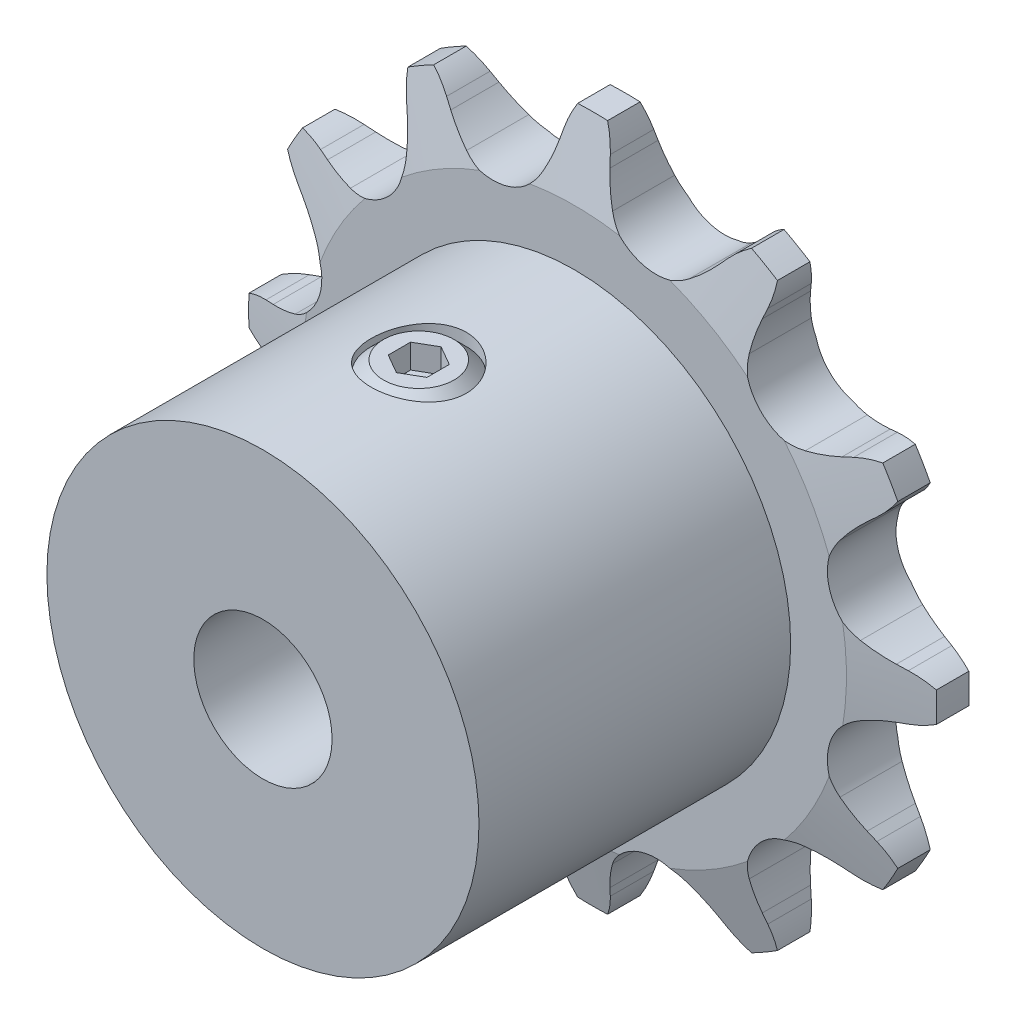
SolidWorks part; units mm, degrees
ref_plane "Front Plane" through (0, 0, 0) normal (0, 0, 1) x (1, 0, 0)
ref_plane "Top Plane" through (0, 0, 0) normal (0, 1, 0) x (1, 0, 0)
ref_plane "Right Plane" through (0, 0, 0) normal (1, 0, 0) x (0, 0, -1)
sketch "Sketch0" plane through (0, 0, 0) normal (0, 0, 1) x (1, 0, 0)
  line L0 (1.8732, -6.9911) -> (0, 0) construction
  line L1 (0, 0) -> (5.1178, -5.1178) construction
  line L2 (0, 0) -> (-1.8732, -6.9911) construction
  line L3 (1.8732, -6.9911) -> (5.1178, -5.1178) construction
  line L4 (1.8732, -6.9911) -> (-1.8732, -6.9911) construction
  line L5 (3.2269, -6.6528) -> (3.077, -6.4844)
  line L6 (1.8732, -6.9911) -> (0, -7.493) construction
  line L7 (0.5318, -7.3749) -> (0.5774, -7.1541)
  line L8 (0, -6.9911) -> (0, -8.115) construction
  line L9 (2.554, -6.0189) -> (0.8243, -8.4891) construction
  line L10 (0, 0) -> (0, -6.9911) construction
  line L11 (3.077, -6.4844) -> (0.8243, -8.4891) construction
  line L12 (0, -8.115) -> (0, -8.3482) construction
  line L13 (4.6449, -5.3909) -> (3.2269, -6.6528) construction
  circle A0 centre (0, 0) radius 8.115 construction
  circle A1 centre (0, 0) radius 7.2377 construction
  arc A2 (-1.6812, -8.8559) -> (5.8839, -6.8289) centre (0, 0) ccw
  circle A3 centre (0, 0) radius 8.3482 construction
  circle A4 centre (1.8732, -6.9911) radius 1.143 construction
  arc A7 (2.554, -6.0189) -> (0.7976, -6.4895) centre (1.8732, -6.9911) ccw
  circle A8 centre (1.8732, -6.9911) radius 1.1868 construction
  arc A9 (3.2269, -6.6528) -> (5.8839, -6.8289) centre (4.6449, -5.3909) ccw
  arc A10 (3.077, -6.4844) -> (2.554, -6.0189) centre (0.8243, -8.4891) ccw
  arc A11 (0.5318, -7.3749) -> (-1.6812, -8.8559) centre (-1.3271, -6.9911) cw
  arc A12 (0.5774, -7.1541) -> (0.7976, -6.4895) centre (3.5307, -7.7639) cw
  dimension "D1" = 1.1868
  dimension "Dr" = 2.286
  dimension "Ds" = 2.3736
  dimension "R" = 1.1868
  dimension "Pitch" = 3.7465
  dimension "A" = 40
  dimension "360/N" = 30
  dimension "B" = 13.333
  dimension "ab" = 3.2004
  dimension "J" = 1.1239
  dimension "ac" = 1.8288
sketch "Sketch1" plane through (0, 0, 0) normal (1, 0, 0) x (0, 0, -1)
  line L0 (0.7874, 0) -> (-0.7874, 0)
  line L1 (-0.7874, 0) -> (-0.7874, 6.2418)
  line L2 (-0.7874, 6.2418) -> (-0.3191, 8.115)
  line L3 (-0.3191, 8.115) -> (0.3191, 8.115)
  line L4 (0.3191, 8.115) -> (0.7874, 6.2418)
  line L5 (0.7874, 6.2418) -> (0.7874, 0)
  line L7 (0, 8.115) -> (0, 0) construction
  line L8 (-0.7874, 6.2418) -> (0.7874, 6.2418) construction
  line L9 (0, 8.115) -> (0, -8.115) construction
  line L10 (-0.7874, 6.2418) -> (-0.7874, 8.115) construction
  line L11 (-0.7874, 8.115) -> (-0.3191, 8.115) construction
  line L12 (0.3191, 8.115) -> (0.7874, 8.115) construction
  line L13 (0.7874, 8.115) -> (0.7874, 6.2418) construction
  line L22 (0.7874, 0) -> (-7.9438, 0) construction
  line L24 (-0.7874, 0) -> (-0.7874, 4.7368) construction
  dimension "t" = 1.5748
  dimension "g" = 0.4683
  dimension "h" = 1.8732
  dimension "MHD" = 9.4736
  dimension "Width" = 8.7312
revolve "Revolve1" add sketch "Sketch1" angle 360 about L0
extrude "Cut-Extrude1" cut sketch "Sketch0" against normal through all and the other way through all
pattern_circular "CirPattern1" count 12 over 360 about axis through (0, 0, 0) along (0, 0, 1) of "Cut-Extrude1"
sketch "Sketch2" plane through (0, 0, 0) normal (0, 0, 1) x (1, 0, 0)
  line L0 (0, 0) -> (0, 4.9609) construction
  circle A0 centre (0, 0) radius 1.5875 construction
  circle A1 centre (0, 0) radius 4.9609
  circle A2 centre (0, 0) radius 7.8994 construction
  dimension "Bore" = 3.175
  dimension "Hub Dia." = 9.9219
  dimension "OD" = 15.7988
extrude "Boss-Extrude1" add sketch "Sketch2" along normal up to vertex (7.9439 mm away) from surface at 0.7874 starting at face at (0, 0, 0.7874)
sketch "Sketch3" plane through (0, 0, 0) normal (0, 0, 1) x (1, 0, 0)
  circle A0 centre (0, 0) radius 1.5875 construction
  circle A1 centre (0, 0) radius 1.5875
  circle A2 centre (0, 0) radius 7.8994 construction
  circle A3 centre (0, 0) radius 7.8994
extrude "Cut-Extrude2" cut sketch "Sketch3" along normal through all and the other way through all flip side to cut
sketch "Sketch4" plane through (0, 0, 0) normal (1, 0, 0) x (0, 0, -1)
  line L1 (-0.7874, 8.115) -> (-3.1686, 8.115)
  line L2 (-0.7874, 8.115) -> (-0.7874, 4.7368)
  line L3 (-0.7874, 4.7368) -> (-3.1686, 4.7368)
  line L4 (-3.1686, 8.115) -> (-3.1686, 4.7368)
  dimension "D1" = 2.3813
revolve "Cut-Revolve1" [suppressed] cut sketch "Sketch4" angle 360 about L22
ref_plane "Plane1" through (0, 4.9609, 0) normal (0, 1, 0) x (-1, 0, 0)
sketch "Sketch5" plane through (0, 4.9609, 0) normal (0, 1, 0) x (-1, 0, 0)
  line L0 (0, 0) -> (0, 0.7874) construction
  line L1 (0, 7.9438) -> (0, 0.7874) construction
  line L2 (4.9609, 0.7874) -> (-4.9609, 0.7874) construction
  line L3 (1.5875, 7.9438) -> (-1.5875, 7.9438) construction
  circle A0 centre (0, 4.3656) radius 1.0922
  circle A1 centre (0, 4.3656) radius 0.6386 construction
  circle A2 centre (0, 4.3656) radius 0.8087 construction
  dimension "D1" = 0.2835
  dimension "Screw OD" = 2.1844
  dimension "Pitch" = 0.4536
extrude "Cut-Extrude3" cut sketch "Sketch5" against normal up to surface (4.9609 mm away) up to plane "Top Plane"
sketch "Sketch6" plane through (0, 0, 0) normal (1, 0, 0) x (0, 0, -1)
  line L0 (-4.3656, 4.9609) -> (-4.3656, 1.5875)
  line L1 (-4.3656, 1.5875) -> (-5.1743, 1.5875)
  line L2 (-5.1743, 1.5875) -> (-5.4578, 1.871)
  line L3 (-5.4578, 1.871) -> (-5.4578, 4.6775)
  line L4 (-5.4578, 4.6775) -> (-5.1743, 4.9609)
  line L5 (-5.1743, 4.9609) -> (-4.3656, 4.9609)
  line L6 (-4.3656, 1.5875) -> (-4.3656, 0) construction
  line L7 (-4.3656, 0) -> (0, 0) construction
  line L10 (-5.4578, 1.5875) -> (-7.9438, 1.5875) construction
  line L11 (-5.4578, 4.6775) -> (-5.4578, 4.9609) construction
  line L12 (-5.4578, 4.9609) -> (-5.1743, 4.9609) construction
revolve "Revolve2" add sketch "Sketch6" angle 360 about L6
sketch "Sketch7" plane through (0, 4.9609, 0) normal (0, 1, 0) x (1, 0, 0)
  line L1 (0, -3.8524) -> (-0.4445, -4.109)
  line L2 (-0.4445, -4.109) -> (-0.4445, -4.6223)
  line L3 (-0.4445, -4.6223) -> (0, -4.8789)
  line L4 (0, -4.8789) -> (0.4445, -4.6223)
  line L5 (0.4445, -4.6223) -> (0.4445, -4.109)
  line L6 (0.4445, -4.109) -> (0, -3.8524)
  circle A0 centre (0, -4.3656) radius 0.4445 construction
  dimension "Hex" = 0.889
extrude "Cut-Extrude4" cut sketch "Sketch7" against normal blind 0.5556
equation "\"360/N@Sketch0\" = 360/\"Teeth@CirPattern1\""
equation "\"Ds@Sketch0\" = 1.005 * \"Dr@Sketch0\" + 0.003"
equation "\"R@Sketch0\" = 1/2 * \"Ds@Sketch0\""
equation "\"A@Sketch0\" = 35 +  ( 60 / \"Teeth@CirPattern1\" ) "
equation "\"B@Sketch0\" = 18 -  ( 56 / \"Teeth@CirPattern1\" )"
equation "\"ac@Sketch0\" = 0.8 * \"Dr@Sketch0\""
equation "\"ab@Sketch0\" = 1.4 * \"Dr@Sketch0\""
equation "\"J@Sketch0\" = 0.3 * \"Pitch@Sketch0\""
equation "\"h@Sketch1\" = \"Pitch@Sketch0\" / 2"
equation "\"g@Sketch1\" = \"h@Sketch1\" / 4"
equation "\"MHD@Sketch1\" = \"Pitch@Sketch0\" * ( cotan ( 180 / \"Teeth@CirPattern1\" ) - 1 ) - 0.030"
equation "\"D1@Cut-Extrude4\" = \"Hex@Sketch7\" * 5 / 8"
equation "\"D1@Sketch5\" = \"Pitch@Sketch5\" * 5 / 8"
